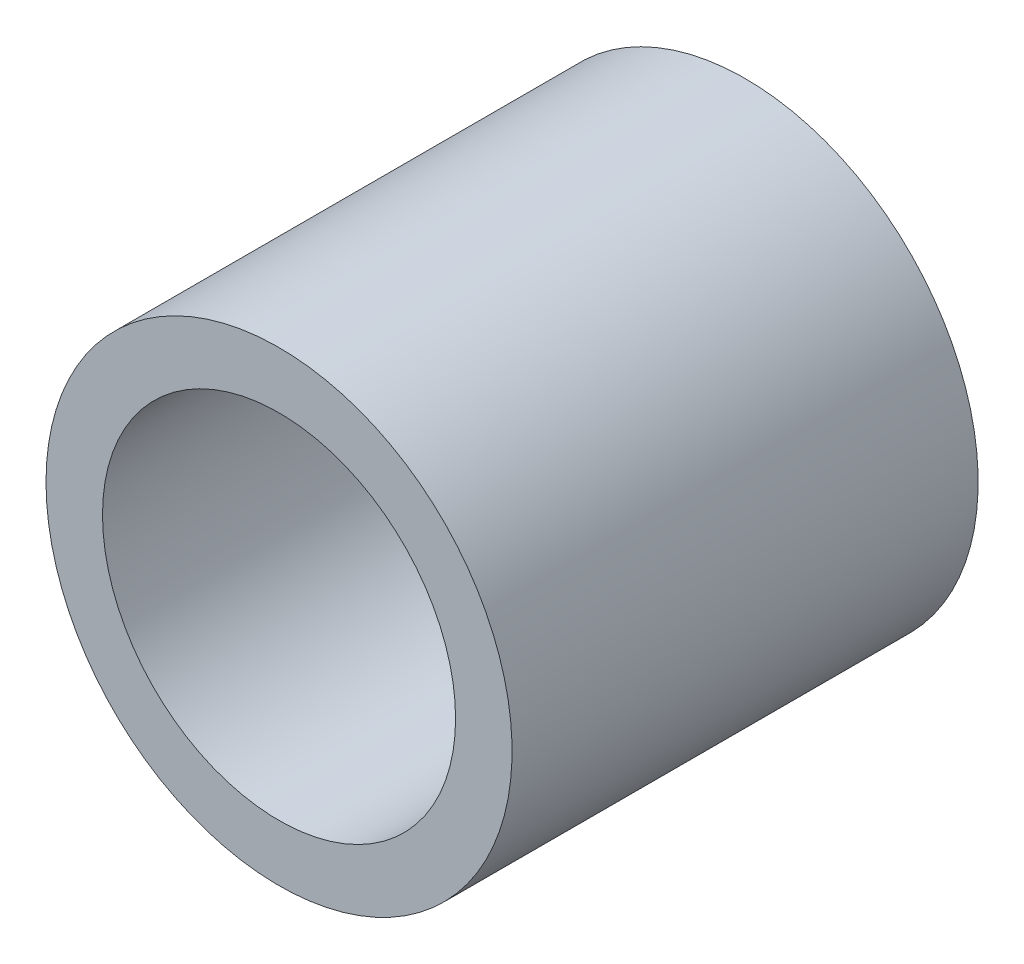
SolidWorks part; units mm, degrees
ref_plane "Front Plane" through (0, 0, 0) normal (0, 0, 1) x (1, 0, 0)
ref_plane "Top Plane" through (0, 0, 0) normal (0, 1, 0) x (1, 0, 0)
ref_plane "Right Plane" through (0, 0, 0) normal (1, 0, 0) x (0, 0, -1)
sketch "Sketch1" plane through (0, 0, 0) normal (0, 0, 1) x (1, 0, 0)
  circle A0 centre (0, 0) radius 4.95
  circle A1 centre (0, 0) radius 3.75
  dimension "D1" = 7.5
  dimension "D2" = 9.9
extrude "Boss-Extrude1" add sketch "Sketch1" along normal blind 9.9
